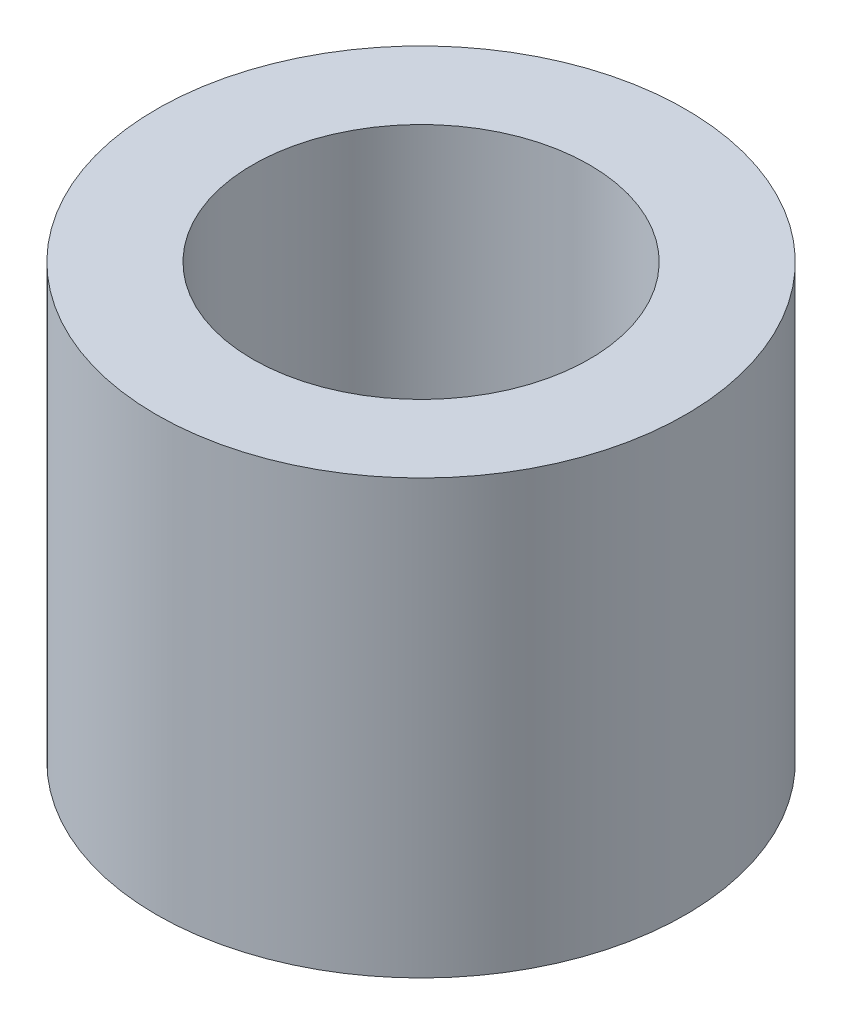
SolidWorks part; units mm, degrees
ref_plane "前视基准面" through (0, 0, 0) normal (0, 0, 1) x (1, 0, 0)
ref_plane "上视基准面" through (0, 0, 0) normal (0, 1, 0) x (1, 0, 0)
ref_plane "右视基准面" through (0, 0, 0) normal (1, 0, 0) x (0, 0, -1)
other "Configuration Table"
sketch "草图1" plane through (0, 0, 0) normal (0, 1, 0) x (1, 0, 0)
  circle A0 centre (0, 0) radius 1.75
  circle A1 centre (0, 0) radius 2.75
  dimension "D1" = 5.5
  dimension "D2" = 3.5
extrude "凸台-拉伸1" add sketch "草图1" along normal blind 4.5
